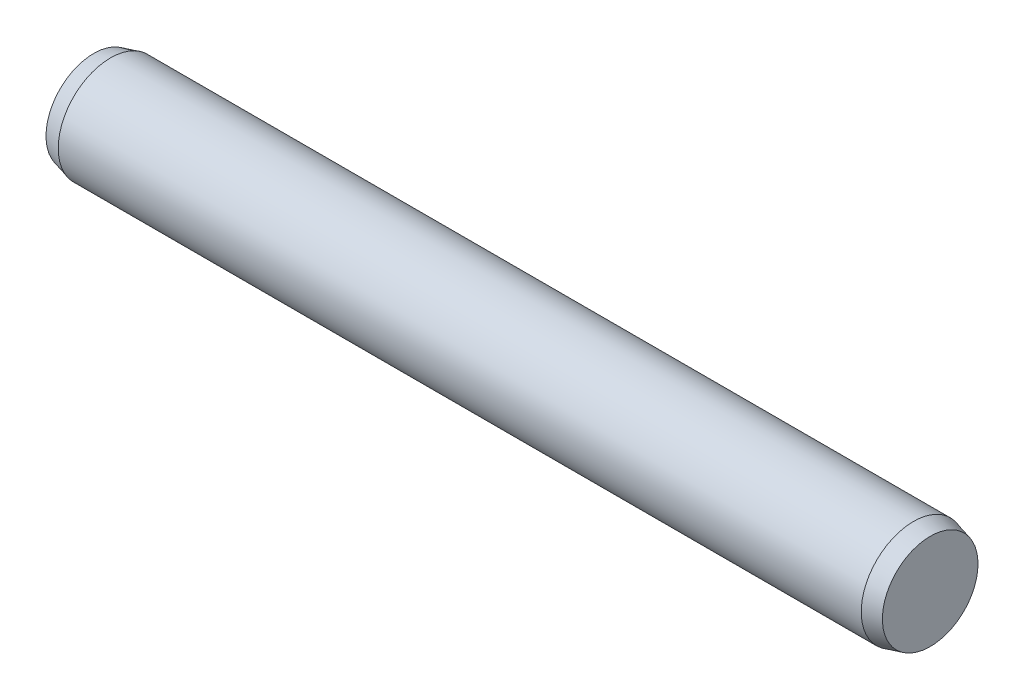
SolidWorks part; units mm, degrees
ref_plane "Front Plane" through (0, 0, 0) normal (0, 0, 1) x (1, 0, 0)
ref_plane "Top Plane" through (0, 0, 0) normal (0, 1, 0) x (1, 0, 0)
ref_plane "Right Plane" through (0, 0, 0) normal (1, 0, 0) x (0, 0, -1)
sketch "Sketch1" plane through (0, 0, 0) normal (0, 0, 1) x (1, 0, 0)
  line L0 (-19.2, 0) -> (19.2, 0) construction
  line L1 (19.2, 2.5) -> (19.2, -2.5) construction
  line L2 (-19.2, 2.5) -> (-19.2, -2.5) construction
  line L3 (20, 2.5) -> (20, -2.5) construction
  line L4 (-20, 2.5) -> (-20, -2.5) construction
  line L5 (-19.2, 0) -> (-20, 0) construction
  line L6 (19.2, 0) -> (20, 0) construction
  point P11 (15, 0)
  point P21 (-15, 0)
  dimension "Dia" = 5
  dimension "C" = 0.8
  dimension "D1" = 0.8
  dimension "Length" = 40
  dimension "D2" = 5
  dimension "D3" = 5
sketch "Sketch2" plane through (0, 0, 0) normal (1, 0, 0) x (0, 0, -1)
  circle A0 centre (0, 0) radius 2.5
extrude "Extrude1" add sketch "Sketch2" against normal up to vertex (19.2 mm away) and the other way up to vertex (19.2 mm away) up to point (-19.2, 2.5, 0) other way up to point (19.2, 2.5, 0)
sketch "Sketch3" plane through (19.2, 0, 0) normal (1, 0, 0) x (0, 0, -1)
  circle A1 centre (0, 0) radius 2.5
  circle A2 centre (0, 0) radius 2.5
  dimension "D1" = 0
extrude "Extrude2" add sketch "Sketch3" along normal up to vertex (0.8 mm away) draft 15 up to point (20, 0, 0)
sketch "Sketch4" plane through (-19.2, 0, 0) normal (-1, 0, 0) x (0, 0, 1)
  circle A1 centre (0, 0) radius 2.5
  circle A2 centre (0, 0) radius 2.5
  dimension "D1" = 0
extrude "Extrude3" add sketch "Sketch4" along normal up to vertex (0.8 mm away) draft 15 up to point (-20, 0, 0)
sketch "Sketch5" plane through (0, 0, 0) normal (1, 0, 0) x (0, 0, -1)
  line L0 (-2.5, 0) -> (2.5, 0) construction
  point P4 (0, 0)
  dimension "D1" = 5
equation "\"D1@Sketch1\" = \"C@Sketch1\""
equation "\"D1@Sketch5\" = \"Dia@Sketch1\""
equation "\"D2@Sketch1\"=\"Dia@Sketch1\""
equation "\"D3@Sketch1\"=\"D2@Sketch1\""
